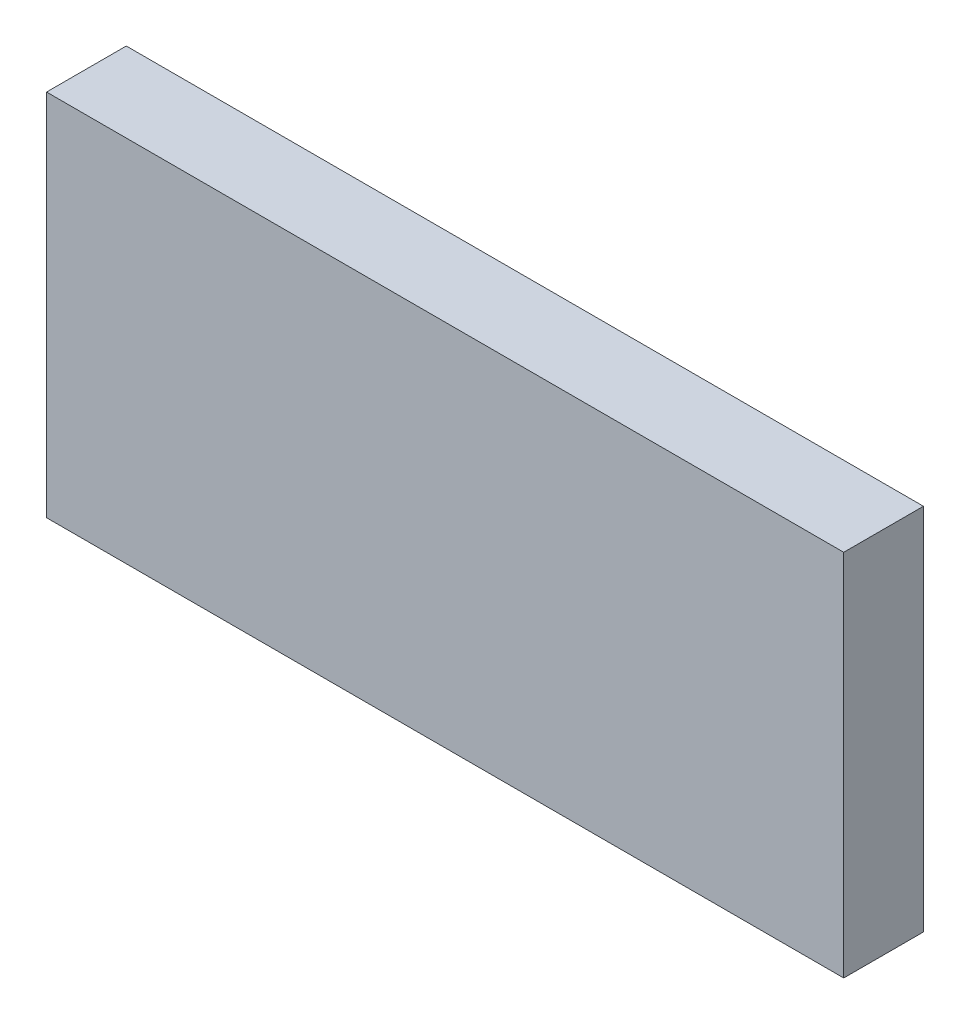
SolidWorks part; units mm, degrees
ref_plane "Front Plane" through (0, 0, 0) normal (0, 0, 1) x (1, 0, 0)
ref_plane "Top Plane" through (0, 0, 0) normal (0, 1, 0) x (1, 0, 0)
ref_plane "Right Plane" through (0, 0, 0) normal (1, 0, 0) x (0, 0, -1)
sketch "Sketch1" plane through (0, 0, 0) normal (0, 0, 1) x (1, 0, 0)
  line L1 (-20, 9.25) -> (20, 9.25)
  line L2 (-20, 9.25) -> (-20, -9.25)
  line L3 (-20, -9.25) -> (20, -9.25)
  line L4 (20, 9.25) -> (20, -9.25)
  line L5 (-20, 9.25) -> (20, -9.25) construction
  line L6 (-20, -9.25) -> (20, 9.25) construction
  point P0 (0, 0)
  dimension "D1" = 40
  dimension "D2" = 18.5
extrude "Boss-Extrude1" add sketch "Sketch1" along normal blind 4
